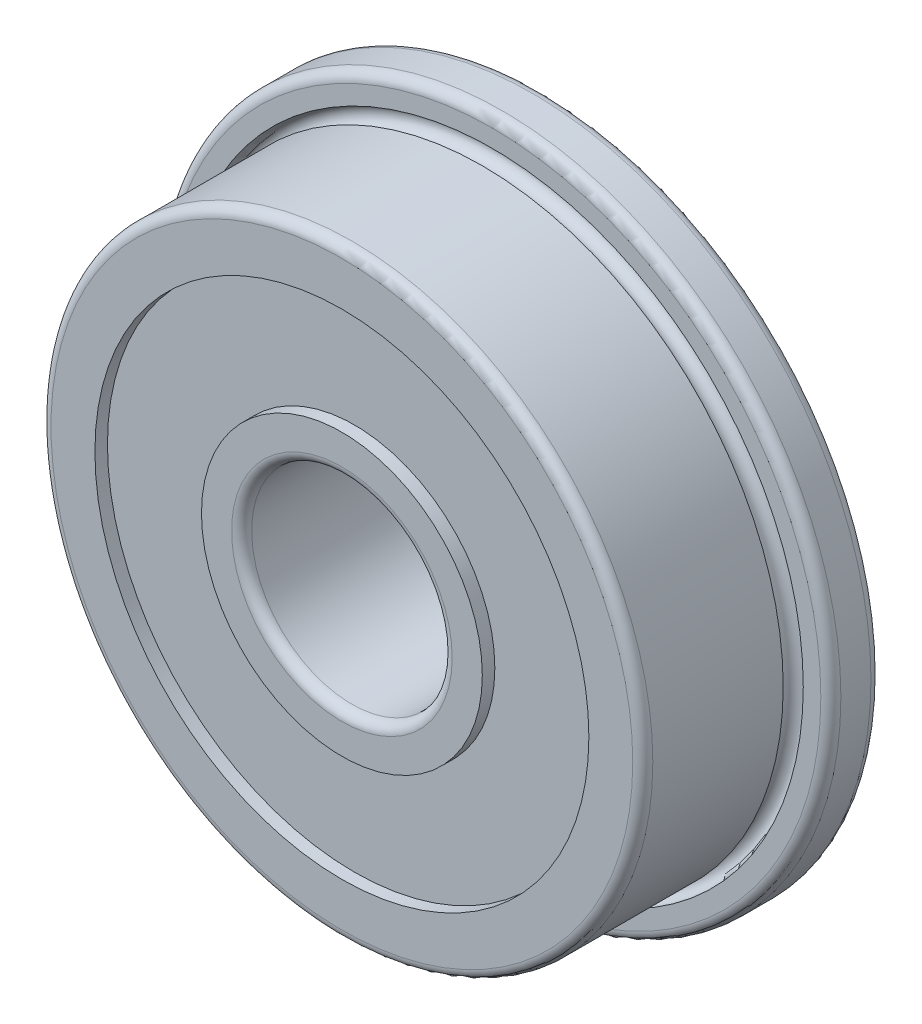
SolidWorks part; units mm, degrees
material "1.4301 (X5CrNi18-10)"
ref_plane "Plan de face" through (0, 0, 0) normal (0, 0, 1) x (1, 0, 0)
ref_plane "Plan de dessus" through (0, 0, 0) normal (0, 1, 0) x (1, 0, 0)
ref_plane "Plan de droite" through (0, 0, 0) normal (1, 0, 0) x (0, 0, -1)
ref_plane "Plan1" through (0, 0, 0) normal (1, 0, 0) x (0, 0, -1)
sketch "Esquisse1" plane through (0, 0, 0) normal (1, 0, 0) x (0, 0, -1)
  line L0 (0, 5.8) -> (0, 4.925)
  line L1 (0, 4.925) -> (0.25, 4.925)
  line L2 (0.25, 4.925) -> (0.25, 2.8)
  line L3 (0.25, 2.8) -> (0, 2.8)
  line L4 (0, 2.8) -> (0, 2.2)
  line L5 (0.2, 2) -> (3.8, 2)
  line L6 (4, 2.2) -> (4, 2.8)
  line L7 (4, 2.8) -> (3.75, 2.8)
  line L8 (3.75, 2.8) -> (3.75, 4.925)
  line L9 (3.75, 4.925) -> (4, 4.925)
  line L10 (4, 4.925) -> (4, 6.55)
  line L11 (3.8, 6.75) -> (3.2, 6.75)
  line L12 (3, 6.55) -> (3, 6.2)
  line L13 (2.8, 6) -> (0.2, 6)
  line L14 (4, 0) -> (0, 0) construction
  arc A0 (0, 2.2) -> (0.2, 2) centre (0.2, 2.2) ccw
  arc A1 (3.8, 2) -> (4, 2.2) centre (3.8, 2.2) ccw
  arc A2 (4, 6.55) -> (3.8, 6.75) centre (3.8, 6.55) ccw
  arc A3 (3.2, 6.75) -> (3, 6.55) centre (3.2, 6.55) ccw
  arc A4 (3, 6.2) -> (2.8, 6) centre (3, 6) cw
  arc A5 (0.2, 6) -> (0, 5.8) centre (0.2, 5.8) ccw
revolve "Révolution1" add sketch "Esquisse1" angle 360 about L14
